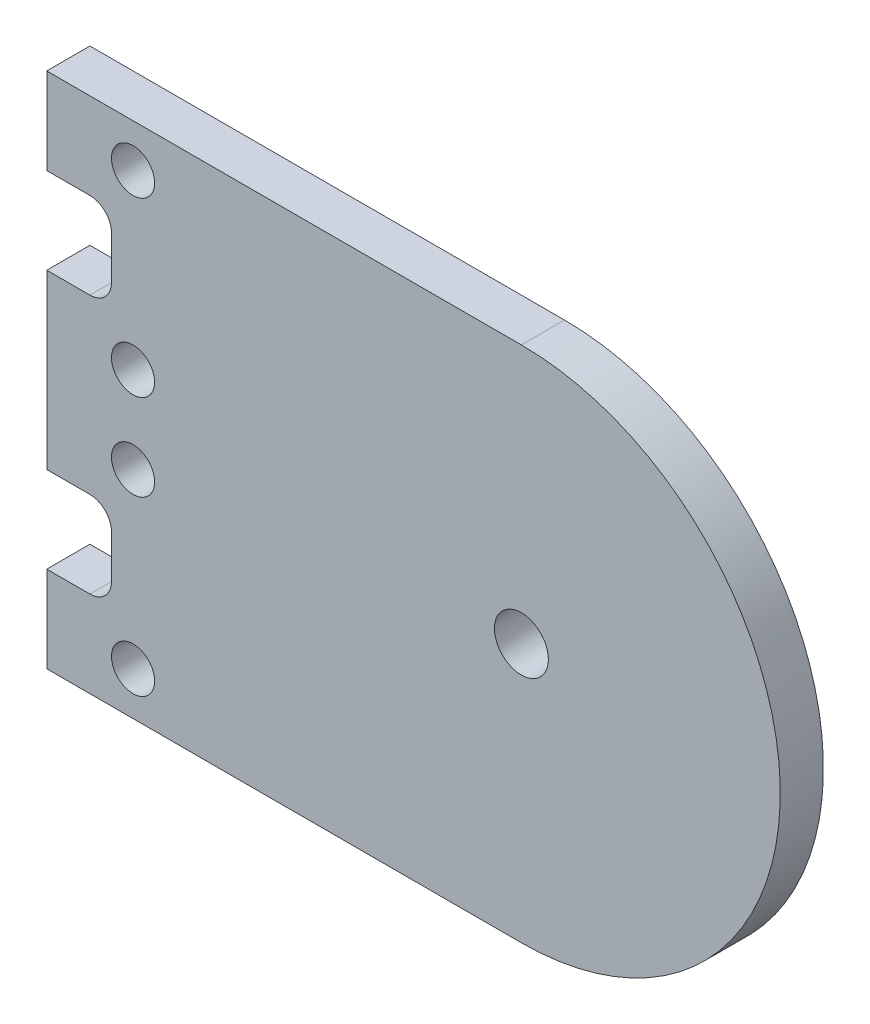
SolidWorks part; units mm, degrees
material "自訂玻璃纖維"
ref_plane "前基準面" through (0, 0, 0) normal (0, 0, 1) x (1, 0, 0)
ref_plane "上基準面" through (0, 0, 0) normal (0, 1, 0) x (1, 0, 0)
ref_plane "右基準面" through (0, 0, 0) normal (1, 0, 0) x (0, 0, -1)
sketch "草圖1" plane through (0, 0, 0) normal (0, 0, 1) x (1, 0, 0)
  line L0 (-38.0931, 13.879) -> (-16.0931, 13.879)
  line L1 (-38.0931, 13.879) -> (-38.0931, 9.879)
  line L2 (-38.0931, -10.121) -> (-16.0931, -10.121)
  line L3 (-38.0931, 9.879) -> (-36.0931, 9.879)
  line L4 (-38.0931, 5.879) -> (-38.0931, -2.121)
  line L5 (-36.0931, 5.879) -> (-38.0931, 5.879)
  line L6 (-35.0931, 8.879) -> (-35.0931, 6.879)
  line L8 (-35.0931, -5.121) -> (-35.0931, -3.121)
  line L9 (-36.0931, -2.121) -> (-38.0931, -2.121)
  line L10 (-38.0931, -6.121) -> (-36.0931, -6.121)
  line L11 (-38.0931, -6.121) -> (-38.0931, -10.121)
  arc A0 (-16.0931, -10.121) -> (-16.0931, 13.879) centre (-16.0931, 1.879) ccw
  circle A1 centre (-16.0931, 1.879) radius 1.25
  circle A2 centre (-34.0931, 11.879) radius 1
  circle A3 centre (-34.0931, 3.879) radius 1
  circle A4 centre (-34.0931, -8.121) radius 1
  circle A5 centre (-34.0931, -0.121) radius 1
  arc A6 (-36.0931, 9.879) -> (-35.0931, 8.879) centre (-36.0931, 8.879) cw
  arc A7 (-35.0931, 6.879) -> (-36.0931, 5.879) centre (-36.0931, 6.879) cw
  arc A8 (-35.0931, -3.121) -> (-36.0931, -2.121) centre (-36.0931, -3.121) ccw
  arc A9 (-36.0931, -6.121) -> (-35.0931, -5.121) centre (-36.0931, -5.121) ccw
  dimension "D3" = 2.5
  dimension "D4" = 8
  dimension "D5" = 4
  dimension "D6" = 2
  dimension "D8" = 2
  dimension "D9" = 2
  dimension "D10" = 2
  dimension "D11" = 2
  dimension "D1" = 24
  dimension "D2" = 22
  dimension "D7" = 8
extrude "填料-伸長1" add sketch "草圖1" along normal blind 2
